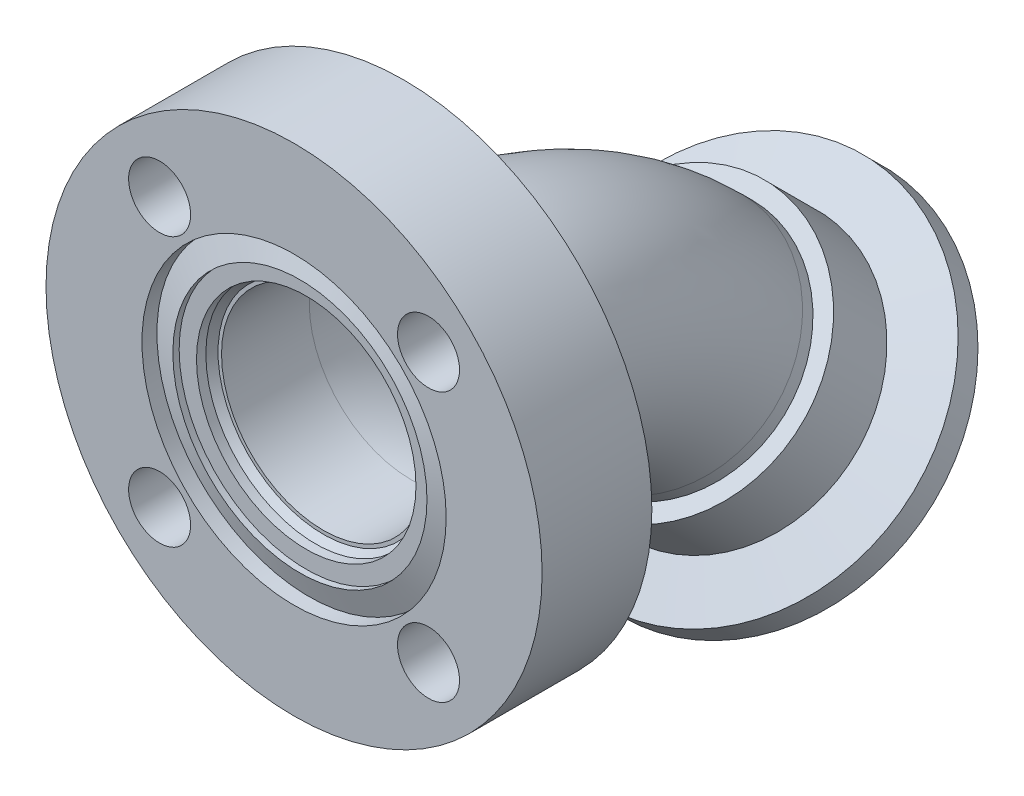
SolidWorks part; units mm, degrees
ref_plane "PL-01 Front" through (0, 0, 0) normal (0, 0, 1) x (1, 0, 0)
ref_plane "PL-02 Top" through (0, 0, 0) normal (0, 1, 0) x (1, 0, 0)
ref_plane "PL-03 Right" through (0, 0, 0) normal (1, 0, 0) x (0, 0, -1)
sketch "Sketch4" plane through (0, 0, 0) normal (1, 0, 0) x (0, 0, -1)
  line L0 (3.175, 0) -> (12.7, 0) construction
  line L1 (39.6408, -11.1592) -> (46.376, -17.8944) construction
  arc A0 (12.7, 0) -> (39.6408, -11.1592) centre (12.7, -38.1) cw construction
  point P0 (35.306, -34.925)
  dimension "D2" = 38.1
  dimension "D4" = 9.525
  dimension "D1" = 12.7
  dimension "D3" = 9.525
  dimension "D6" = 45
  dimension "D7" = 35.306
  dimension "D8" = 34.925
ref_plane "Plane1" through (0, 0, -3.175) normal (0, 0, -1) x (-1, 0, 0)
sketch "Sketch1" plane through (0, 0, 0) normal (1, 0, 0) x (0, 0, -1)
  line L0 (0, 0) -> (48.0962, 0) construction
  line L1 (0, 26.924) -> (0, 16.51)
  line L2 (0, 26.924) -> (11.9126, 26.924)
  line L3 (11.9126, 26.924) -> (11.9126, 11.1125)
  line L4 (1.3208, 11.9126) -> (2.3368, 11.9126)
  line L5 (2.3368, 11.9126) -> (3.7226, 11.1125)
  line L6 (3.7226, 11.1125) -> (11.9126, 11.1125)
  line L7 (0, 16.51) -> (1.6242, 16.51)
  line L10 (1.6242, 16.51) -> (0.635, 13.7922)
  line L11 (0.635, 13.7922) -> (1.3208, 13.7922)
  line L12 (1.3208, 13.7922) -> (1.3208, 11.9126)
  dimension "D1" = 27.5844
  dimension "D2" = 53.848
  dimension "D3" = 33.02
  dimension "D4" = 11.9126
  dimension "D5" = 22.225
  dimension "D6" = 20
  dimension "D7" = 0.635
  dimension "D8" = 1.3208
  dimension "D9" = 23.8252
  dimension "D10" = 1.016
  dimension "D11" = 30
revolve "Revolve1" add sketch "Sketch1" angle 360 about L0
sketch "Sketch3" plane through (0, 0, 0) normal (0, 0, 1) x (1, 0, 0)
  line L0 (0, 0) -> (19.0389, 19.0373) construction
  circle A0 centre (14.5935, 14.5923) radius 3.3655
  circle A1 centre (0, 0) radius 26.924 construction
  dimension "D1" = 6.731
  dimension "D2" = 20.6375
  dimension "D3" = 14.5923
  dimension "D4" = 14.5935
extrude "Cut-Extrude2" cut sketch "Sketch3" against normal through all
pattern_circular "CirPattern1" count 4 over 360 about axis through (0, 0, 0) along (0, 0, 1) of "Cut-Extrude2"
sketch "Sketch6" plane through (0, 0, -3.175) normal (0, 0, 1) x (1, 0, 0)
  circle A0 centre (0, 0) radius 11.049
  circle A1 centre (0, 0) radius 12.7
  dimension "D1" = 1.651
  dimension "D2" = 25.4
sketch "Sketch5" plane through (0, 0, 0) normal (1, 0, 0) x (0, 0, -1)
  line L0 (3.175, 0) -> (12.7, 0) construction
  line L1 (39.6408, -11.1592) -> (46.376, -17.8944) construction
  line L2 (3.175, 0) -> (12.7, 0)
  line L3 (39.6408, -11.1592) -> (46.376, -17.8944)
  arc A0 (39.6408, -11.1592) -> (12.7, 0) centre (12.7, -38.1) ccw construction
  arc A1 (39.6408, -11.1592) -> (12.7, 0) centre (12.7, -38.1) ccw
sweep "Sweep2" add profiles "Sketch6" path "Sketch5"
sketch "Sketch7" plane through (0, 0, 0) normal (1, 0, 0) x (0, 0, -1)
  line L0 (56.4319, -10.9995) -> (57.2241, -10.2073)
  line L1 (57.2241, -10.2073) -> (59.0202, -12.0034)
  line L2 (59.0202, -12.0034) -> (63.8875, -7.1361)
  line L3 (63.8875, -7.1361) -> (61.7322, -4.9808)
  line L4 (61.7322, -4.9808) -> (56.8335, -7.8091)
  line L5 (56.8335, -7.8091) -> (51.0437, -2.0193)
  line L6 (51.0437, -2.0193) -> (49.2477, -3.8153)
  line L7 (49.2477, -3.8153) -> (56.4319, -10.9995)
  line L9 (46.376, -17.8944) -> (72.0427, -43.5612) construction
  line L10 (39.6408, -11.1592) -> (46.376, -17.8944) construction
  dimension "D1" = 29.0521
  dimension "D2" = 2.54
  dimension "D3" = 39.9796
  dimension "D4" = 26.2128
  dimension "D5" = 2.54
  dimension "D6" = 3.048
  dimension "D7" = 15
  dimension "D8" = 4.7752
  dimension "D9" = 12.7
revolve "Revolve2" add sketch "Sketch7" angle 360 about L9
